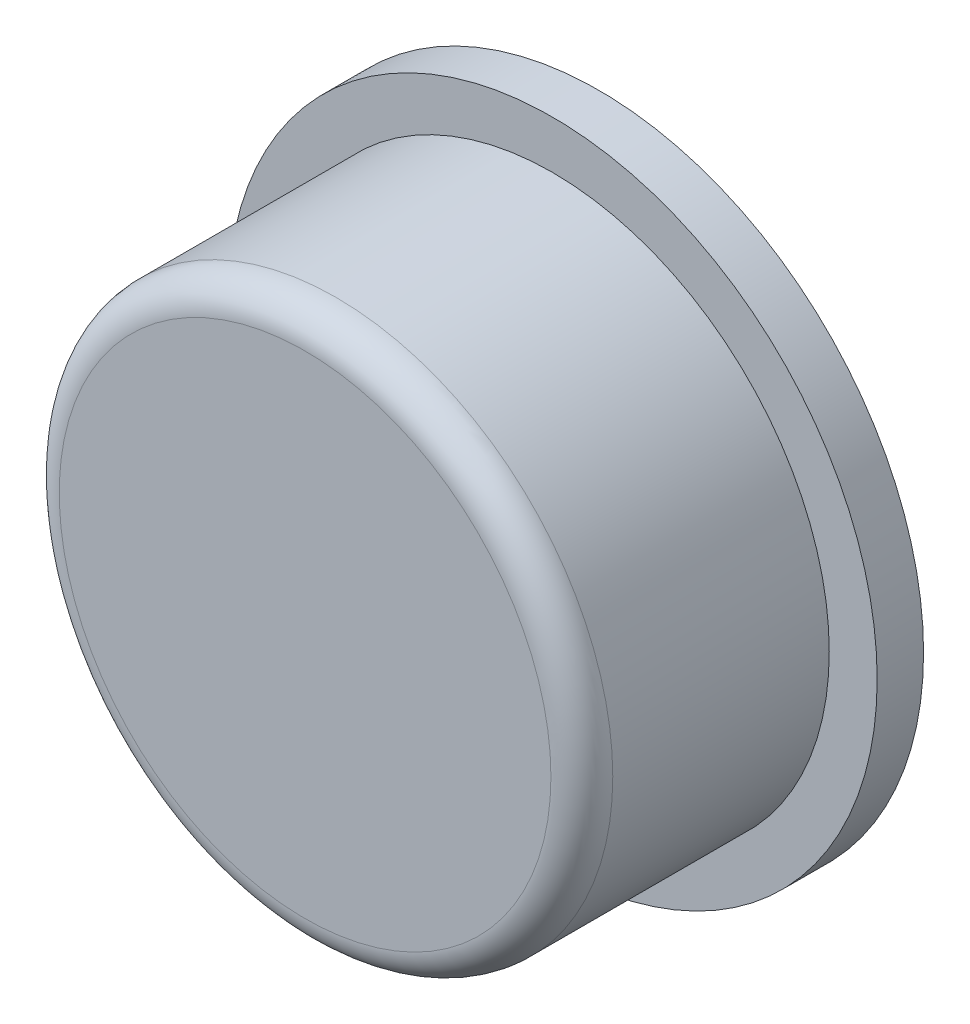
SolidWorks part; units mm, degrees
material "AISI 316 Stainless Steel Sheet (SS)"
ref_plane "Front Plane" through (0, 0, 0) normal (0, 0, 1) x (1, 0, 0)
ref_plane "Top Plane" through (0, 0, 0) normal (0, 1, 0) x (1, 0, 0)
ref_plane "Right Plane" through (0, 0, 0) normal (1, 0, 0) x (0, 0, -1)
sketch "Sketch1" plane through (0, 0, 0) normal (0, 1, 0) x (1, 0, 0)
  line L0 (0, 21.6762) -> (0, 12) construction
  line L1 (0, 0) -> (7.95, 0)
  line L2 (8.95, 1) -> (8.95, 8)
  line L3 (8.95, 8) -> (10.5, 8)
  line L4 (10.5, 8) -> (10.5, 9.5)
  line L5 (10.5, 9.5) -> (3.7081, 9.5)
  line L6 (0, 4) -> (0, -8.8837) construction
  line L7 (0, 0) -> (0, 12)
  arc A0 (3.7081, 9.5) -> (0, 12) centre (0, 8) ccw
  arc A1 (8.95, 1) -> (7.95, 0) centre (7.95, 1) cw
  point P11 (0, 0)
  point P12 (0, 0)
  point P16 (8.95, 0)
  dimension "D1" = 8
  dimension "D7" = 1
  dimension "D2" = 8.95
  dimension "D3" = 8
  dimension "D4" = 1.5
  dimension "D5" = 10.5
  dimension "D6" = 8
revolve "Revolve1" add sketch "Sketch1" angle 360 about L7
